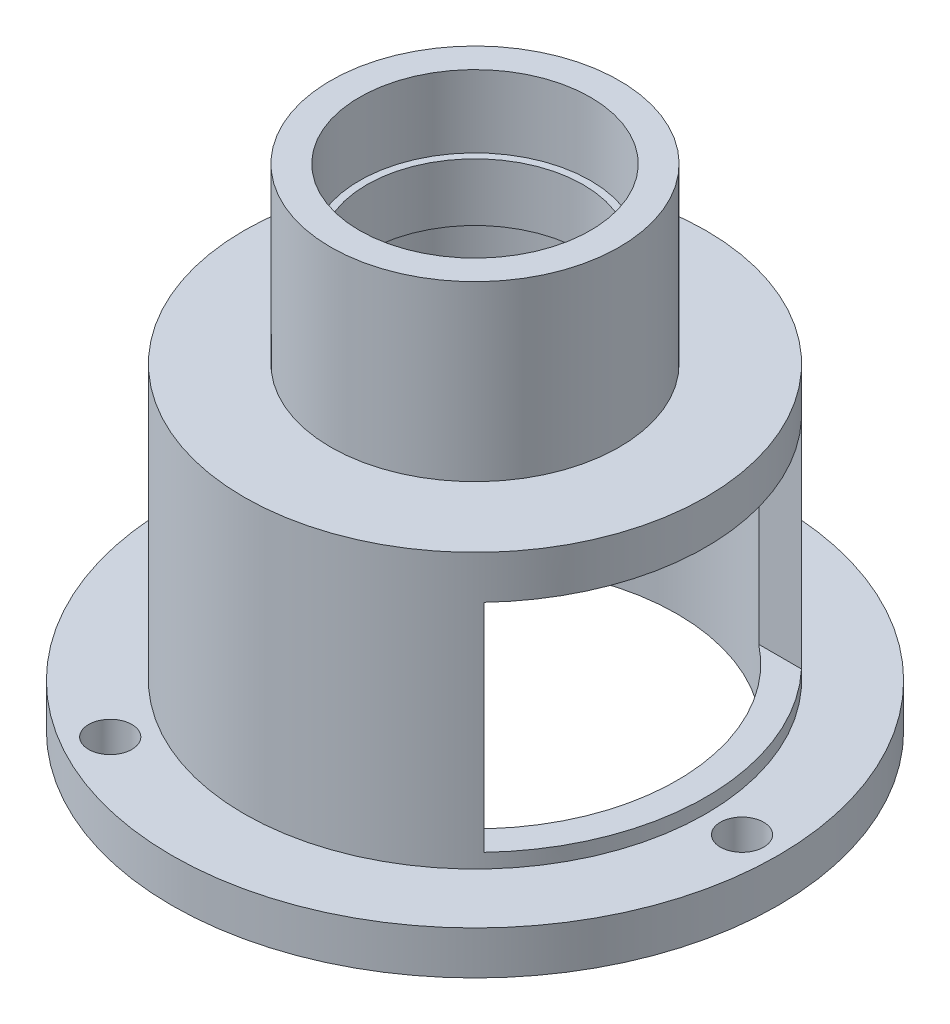
SolidWorks part; units mm, degrees
ref_plane "前视基准面" through (0, 0, 0) normal (0, 0, 1) x (1, 0, 0)
ref_plane "上视基准面" through (0, 0, 0) normal (0, 1, 0) x (1, 0, 0)
ref_plane "右视基准面" through (0, 0, 0) normal (1, 0, 0) x (0, 0, -1)
sketch "草图1" plane through (0, 0, 0) normal (0, 1, 0) x (1, 0, 0)
  circle A0 centre (0, 0) radius 16
  circle A2 centre (0, 0) radius 8
  dimension "D1" = 32
  dimension "D3" = 16
extrude "凸台-拉伸1" add sketch "草图1" along normal blind 14
sketch "草图2" plane through (0, 14, 0) normal (0, 1, 0) x (1, 0, 0)
  circle A0 centre (0, 0) radius 10
  circle A1 centre (0, 0) radius 20
  dimension "D1" = 20
extrude "切除-拉伸1" cut sketch "草图2" against normal blind 12
sketch "草图4" plane through (0, 0, 0) normal (0, -1, 0) x (1, 0, 0)
  circle A0 centre (0, 0) radius 9.5
  circle A1 centre (0, 0) radius 7.5
  dimension "D1" = 19
  dimension "D2" = 15
extrude "凸台-拉伸2" add sketch "草图4" against normal blind 4 from offset 5 offset against normal yes
sketch "草图6" plane through (0, 0, 0) normal (0, -1, 0) x (1, 0, 0)
  circle A1 centre (0, 0) radius 16
  circle A2 centre (0, 0) radius 14
  dimension "D1" = 32
  dimension "D2" = 28
extrude "凸台-拉伸3" add sketch "草图6" along normal blind 17
sketch "草图7" plane through (0, -17, 0) normal (0, -1, 0) x (1, 0, 0)
  circle A0 centre (0, 0) radius 14
  circle A1 centre (0, 0) radius 21
  dimension "D1" = 42
  dimension "D2" = 28
extrude "凸台-拉伸4" add sketch "草图7" along normal blind 3
sketch "草图8" plane through (0, -17, 0) normal (0, 1, 0) x (1, 0, 0)
  line L0 (0, 0) -> (35.7233, 0) construction
  circle A0 centre (0, 0) radius 18.5 construction
  circle A1 centre (18.5, 0) radius 1.5
  circle A2 centre (-9.25, -16.0215) radius 1.5
  circle A3 centre (-9.25, 16.0215) radius 1.5
  point P13 (0, 0)
  dimension "D1" = 37
  dimension "D2" = 3
  dimension "D3" = 3
extrude "切除-拉伸4" cut sketch "草图8" against normal blind 10
sketch "草图11" plane through (0, 0, 0) normal (0, 0, 1) x (1, 0, 0)
  line L1 (-1, -1) -> (-16, -1)
  line L2 (-1, -1) -> (-1, -16)
  line L3 (-1, -16) -> (-16, -16)
  line L4 (-16, -1) -> (-16, -16)
  line L5 (-16, 2) -> (-16, -17) construction
  line L6 (0, 0) -> (0, -17) construction
  line L7 (21, -17) -> (-21, -17) construction
  dimension "D1" = 15
  dimension "D2" = 15
  dimension "D3" = 1
extrude "切除-拉伸5" cut sketch "草图11" against normal mid plane 22
mirror "镜向1" about plane through (0, 0, 0) normal (1, 0, 0) of "切除-拉伸5"
